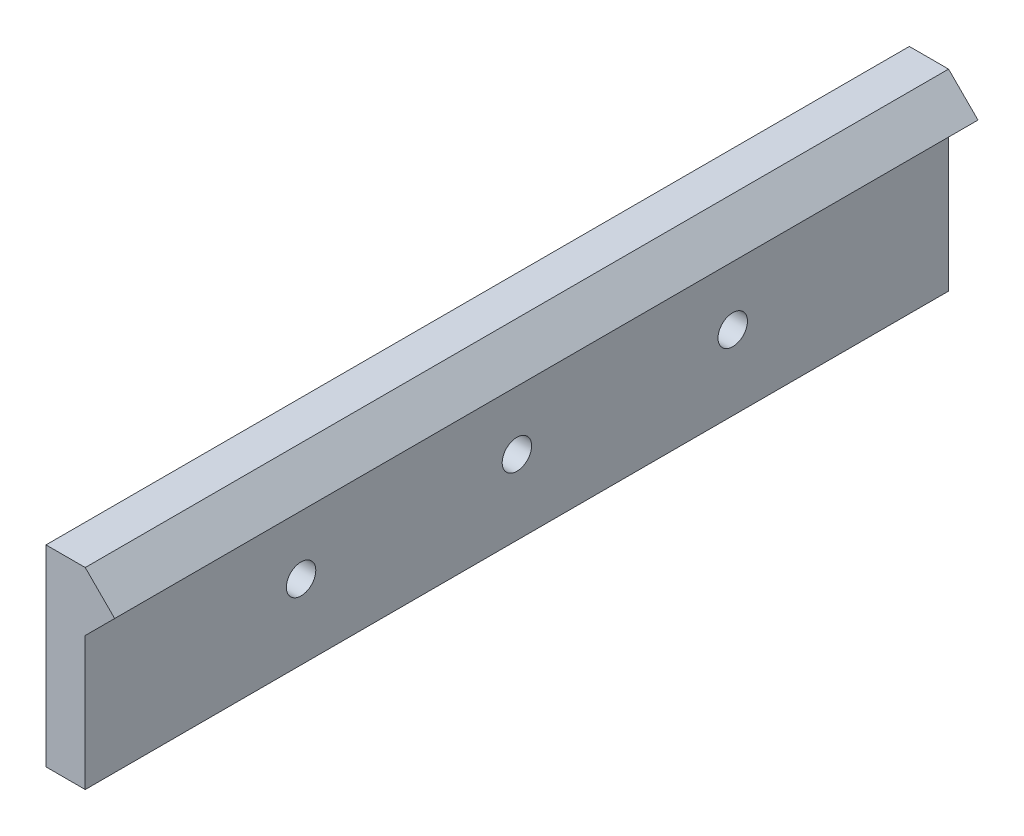
SolidWorks part; units mm, degrees
material "ASTM A36 Steel"
ref_plane "Front Plane" through (0, 0, 0) normal (0, 0, 1) x (1, 0, 0)
ref_plane "Top Plane" through (0, 0, 0) normal (0, 1, 0) x (1, 0, 0)
ref_plane "Right Plane" through (0, 0, 0) normal (1, 0, 0) x (0, 0, -1)
sketch "Sketch1" plane through (0, 0, 0) normal (0, 0, 1) x (1, 0, 0)
  line L0 (-104.5584, 0) -> (104.5584, 0) construction
  line L1 (0, -141.8542) -> (0, 141.8542) construction
  line L2 (6.35, 63.5) -> (15.875, 53.975)
  line L3 (-6.35, 0) -> (6.35, 0) construction
  line L4 (-6.35, 1.27) -> (-6.35, 63.5)
  line L5 (-6.35, 63.5) -> (6.35, 63.5)
  line L10 (6.35, 44.45) -> (15.875, 53.975)
  line L11 (6.35, 63.5) -> (6.35, 0) construction
  line L12 (6.35, 44.45) -> (6.35, 1.27)
  line L13 (-6.35, 1.27) -> (6.35, 1.27)
  point P4 (0, 0)
  point P8 (0, 0)
  point P16 (6.35, 127)
  point P17 (0, 3.175)
  dimension "D1" = 6.35
  dimension "D2" = 12.7
  dimension "D3" = 45
  dimension "D4" = 63.5
  dimension "D5" = 19.05
  dimension "D6" = 45
  dimension "D7" = 1.27
extrude "Boss-Extrude1" add sketch "Sketch1" along normal mid plane 279.4
sketch "Sketch2" plane through (0, 0, 0) normal (1, 0, 0) x (0, 0, -1)
  line L0 (-190.652, 0) -> (190.652, 0) construction
  line L2 (0, -172.5187) -> (0, 172.5187) construction
  circle A0 centre (-69.85, 25.4) radius 4.7625
  circle A1 centre (0, 25.4) radius 4.7625
  circle A2 centre (69.85, 25.4) radius 4.7625
  point P4 (0, 0)
  point P8 (0, 0)
  dimension "D3" = 9.525
  dimension "D1" = 25.4
  dimension "D2" = 69.85
  dimension "D4" = 3
extrude "Cut-Extrude1" cut sketch "Sketch2" against normal mid plane 76.2
